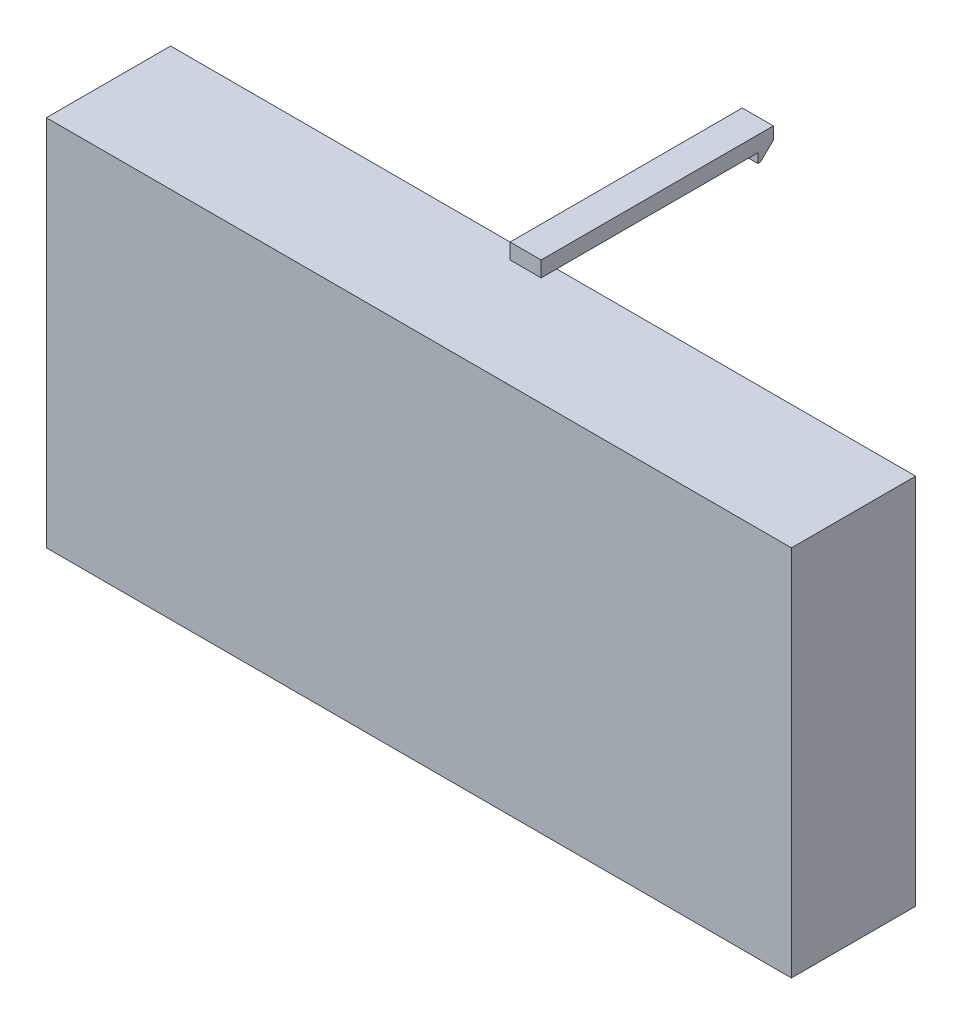
SolidWorks part; units mm, degrees
ref_plane "Front Plane" through (0, 0, 0) normal (0, 0, 1) x (1, 0, 0)
ref_plane "Top Plane" through (0, 0, 0) normal (0, 1, 0) x (1, 0, 0)
ref_plane "Right Plane" through (0, 0, 0) normal (1, 0, 0) x (0, 0, -1)
sketch "Sketch1" plane through (0, 0, 0) normal (0, 0, 1) x (1, 0, 0)
  line L1 (0, 0) -> (304.8, 0)
  line L2 (0, 0) -> (0, 152.4)
  line L3 (0, 152.4) -> (304.8, 152.4)
  line L4 (304.8, 0) -> (304.8, 152.4)
  dimension "D1" = 304.8
  dimension "D2" = 152.4
extrude "Boss-Extrude1" add sketch "Sketch1" along normal blind 50.8
shell "Shell1" thickness 3.175
sketch "Sketch3" plane through (0, 152.4, 0) normal (0, 1, 0) x (1, 0, 0)
  line L0 (152.4, 0) -> (152.4, -50.8) construction
  line L1 (304.8, 0) -> (0, 0) construction
  line L2 (304.8, -50.8) -> (0, -50.8) construction
  line L4 (145.2496, 0) -> (157.9496, 0)
  line L5 (145.2496, 0) -> (145.2496, -6.35)
  line L6 (145.2496, -6.35) -> (157.9496, -6.35)
  line L7 (157.9496, 0) -> (157.9496, -6.35)
  dimension "D1" = 12.7
  dimension "D2" = 6.35
extrude "Boss-Extrude2" add sketch "Sketch3" along normal blind 6.35
sketch "Sketch4" plane through (0, 0, 0) normal (0, 0, -1) x (-1, 0, 0)
  line L7 (-157.9496, 158.75) -> (-145.2496, 158.75)
  line L8 (-157.9496, 158.75) -> (-157.9496, 152.4)
  line L9 (-157.9496, 152.4) -> (-145.2496, 152.4)
  line L10 (-145.2496, 158.75) -> (-145.2496, 152.4)
extrude "Boss-Extrude3" add sketch "Sketch4" along normal blind 88.646
sketch "Sketch5" plane through (0, 152.4, 0) normal (0, -1, 0) x (1, 0, 0)
  line L0 (157.9496, -88.646) -> (157.9496, 0) construction
  line L1 (145.2496, -88.646) -> (157.9496, -88.646)
  line L2 (145.2496, -88.646) -> (145.2496, -82.296)
  line L3 (145.2496, -82.296) -> (157.9496, -82.296)
  line L4 (157.9496, -88.646) -> (157.9496, -82.296)
  dimension "D1" = 6.35
extrude "Boss-Extrude4" add sketch "Sketch5" along normal blind 3.81
sketch "Sketch6" plane through (157.9496, 0, 0) normal (1, 0, 0) x (0, 0, -1)
  line L0 (83.3855, 148.59) -> (88.646, 153.67)
  line L1 (88.646, 148.59) -> (82.296, 148.59) construction
  line L2 (88.646, 158.75) -> (88.646, 148.59) construction
  line L5 (88.646, 153.67) -> (88.646, 148.59)
  line L6 (88.646, 148.59) -> (83.3855, 148.59)
  dimension "D1" = 44
extrude "Cut-Extrude1" cut sketch "Sketch6" against normal up to next
sketch "Sketch7" plane through (0, 0, 0) normal (0, 0, -1) x (-1, 0, 0)
  line L0 (-3.175, 76.2) -> (-304.8, 76.2) construction
  line L1 (-3.175, 149.225) -> (-3.175, 3.175) construction
  line L2 (-304.8, 0) -> (-304.8, 152.4) construction
ref_plane "Plane1" through (0, 76.2, 0) normal (0, -1, 0) x (1, 0, 0)
mirror "Mirror1" about plane through (0, 76.2, 0) normal (0, -1, 0) of "Boss-Extrude2", "Boss-Extrude3", "Boss-Extrude4", "Cut-Extrude1"
equation "\"modulus\"= 435000"
equation "\"safety_factor\"= 3.5"
equation "\"tensile\"= 2.5"
equation "\"axial\"= 7.5"
equation "\"yield\"= 7250"
equation "\"w\"= 0.25"
equation "\"b\"= 0.5"
equation "\"deflection\"= 0.125"
equation "\"length\"= 3.49"
equation "\"area\"= 0.125"
